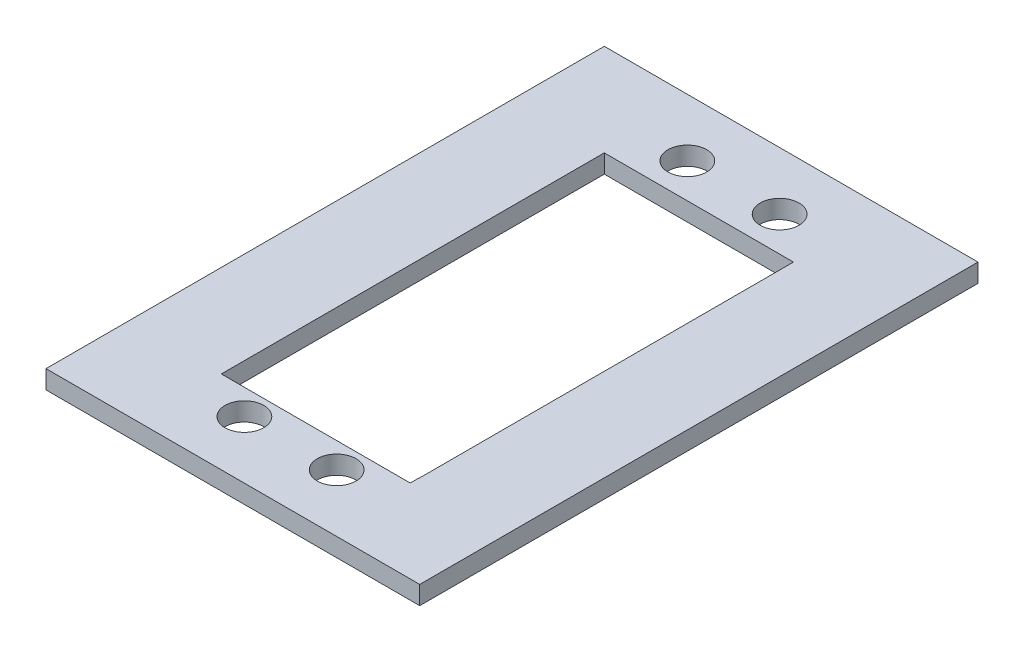
SolidWorks part; units mm, degrees
ref_plane "前视基准面" through (0, 0, 0) normal (0, 0, 1) x (1, 0, 0)
ref_plane "上视基准面" through (0, 0, 0) normal (0, 1, 0) x (1, 0, 0)
ref_plane "右视基准面" through (0, 0, 0) normal (1, 0, 0) x (0, 0, -1)
other "Configuration Table"
sketch "草图1" plane through (0, 0, 0) normal (0, 1, 0) x (1, 0, 0)
  line L0 (-20.25, 30.25) -> (20.25, 30.25)
  line L1 (-10.25, -20.25) -> (10.25, -20.25)
  line L2 (-10.25, -20.25) -> (-10.25, 20.25)
  line L3 (-10.25, 20.25) -> (10.25, 20.25)
  line L4 (10.25, -20.25) -> (10.25, 20.25)
  line L5 (-10.25, -20.25) -> (10.25, 20.25) construction
  line L6 (-10.25, 20.25) -> (10.25, -20.25) construction
  line L7 (20.25, -30.25) -> (20.25, 30.25)
  line L8 (-20.25, -30.25) -> (20.25, -30.25)
  line L9 (-20.25, -30.25) -> (-20.25, 30.25)
  line L10 (-1000, 0) -> (49000, 0) construction
  line L11 (5, 16.5) -> (-5, 16.5)
  line L12 (5, 16.5) -> (5, 24)
  line L13 (5, 24) -> (-5, 24)
  line L14 (-5, 16.5) -> (-5, 24)
  line L15 (5, 16.5) -> (-5, 24) construction
  line L16 (5, 24) -> (-5, 16.5) construction
  line L17 (0.2658, -1000.525) -> (0.2658, 48999.475) construction
  circle A0 centre (-5, 24) radius 2.1
  circle A1 centre (5, 24) radius 2.1
  circle A2 centre (5, -24) radius 2.1
  circle A3 centre (-5, -24) radius 2.1
  point P0 (0, 0)
  point P10 (0, 20.25)
  dimension "D6" = 4.2
  dimension "D7" = 4.2
  dimension "D1" = 40.5
  dimension "D2" = 20.5
  dimension "D4" = 10
  dimension "D5" = 7.5
  dimension "D3" = 10
extrude "凸台-拉伸2" add sketch "草图1" along normal blind 2 contours L9 L8 L7 L0 A2 A1 L12 L3 L4 L1 L2 L14 A0 L13 A3 | A1 L13 A0 L14 L3 L12
sketch "草图3" plane through (0, 2, 0) normal (0, 1, 0) x (1, 0, 0)
  line L1 (-10.25, -20.25) -> (10.2212, -20.25)
  line L2 (-10.25, -20.25) -> (-10.25, -21.25)
  line L3 (-10.25, -21.25) -> (10.2212, -21.25)
  line L4 (10.2212, -20.25) -> (10.2212, -21.25)
  dimension "D1" = 1
extrude "切除-拉伸2" cut sketch "草图3" against normal blind 2
